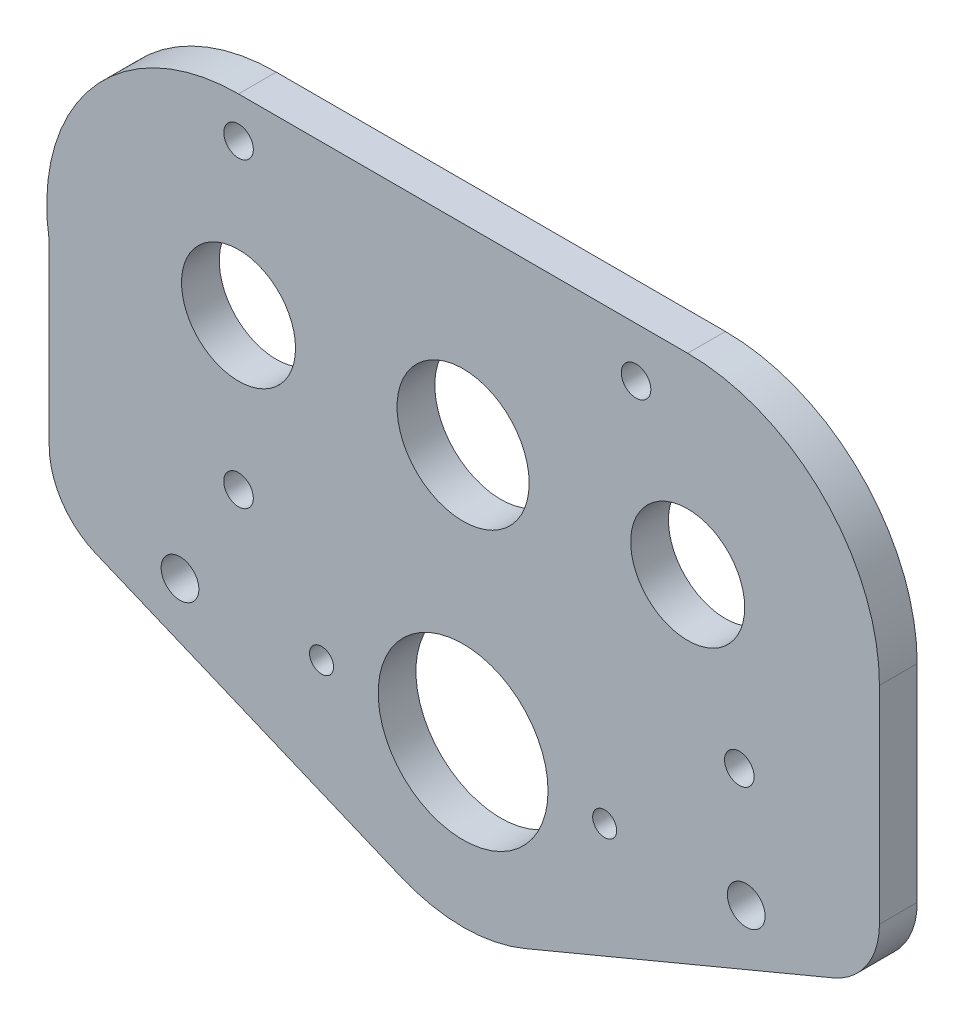
SolidWorks part; units mm, degrees
ref_plane "Front Plane" through (0, 0, 0) normal (0, 0, 1) x (1, 0, 0)
ref_plane "Top Plane" through (0, 0, 0) normal (0, 1, 0) x (1, 0, 0)
ref_plane "Right Plane" through (0, 0, 0) normal (1, 0, 0) x (0, 0, -1)
sketch "Sketch1" plane through (0, 0, 0) normal (0, 0, 1) x (1, 0, 0)
  line L0 (-37.7793, 75.5142) -> (37.7793, 75.5142)
  line L1 (-73.025, -38.1) -> (-73.025, 38.1) construction
  line L2 (-61.8163, -3.4327) -> (-10.3992, -24.9035)
  line L3 (-327.025, 38.1) -> (327.025, 38.1) construction
  line L4 (-327.025, 38.1) -> (-327.025, -38.1) construction
  line L5 (-327.025, -38.1) -> (327.025, -38.1) construction
  line L6 (327.025, 38.1) -> (327.025, -38.1) construction
  line L7 (-327.025, 38.1) -> (327.025, -38.1) construction
  line L8 (-327.025, -38.1) -> (327.025, 38.1) construction
  line L9 (-37.7793, 68.6562) -> (-37.7793, 17.8562) construction
  line L10 (-69.6226, 38.1) -> (-69.6226, 8.2865)
  line L11 (70.0373, 43.2562) -> (70.0373, 8.4595)
  line L12 (62.231, -3.2598) -> (10.3991, -24.9035)
  circle A0 centre (0, 0) radius 14.2875
  circle A1 centre (-37.7793, 43.2562) radius 9.5885
  circle A2 centre (37.7793, 43.2562) radius 9.5885
  circle A3 centre (0, 43.2562) radius 11.1125
  circle A4 centre (-37.7793, 43.2562) radius 32.258 construction
  circle A5 centre (37.7793, 43.2562) radius 32.258 construction
  circle A6 centre (0, 0) radius 6.35 construction
  circle A7 centre (0, 0) radius 39.37 construction
  circle A8 centre (-47.625, 0) radius 3.175
  circle A9 centre (47.625, 0) radius 3.175
  circle A10 centre (0, 0) radius 19.05 construction
  circle A11 centre (0, 43.2562) radius 32.512 construction
  circle A12 centre (-23.8125, 0) radius 2.0193
  circle A13 centre (23.8125, 0) radius 2.0193
  circle A14 centre (0, 0) radius 26.9875 construction
  arc A15 (-10.3992, -24.9035) -> (10.3991, -24.9035) centre (0, 0) ccw
  arc A16 (-69.6226, 38.1) -> (-37.7793, 75.5142) centre (-37.7793, 43.2562) cw
  arc A17 (37.7793, 75.5142) -> (70.0373, 43.2562) centre (37.7793, 43.2562) cw
  circle A18 centre (-37.7793, 68.6562) radius 2.4892
  circle A19 centre (-37.7793, 17.8562) radius 2.4892
  circle A20 centre (37.7793, 68.6562) radius 2.4892 construction
  circle A21 centre (37.7793, 17.8562) radius 2.4892 construction
  circle A22 centre (46.4666, 67.1244) radius 2.4892 [skipped]
  circle A23 centre (54.1061, 62.7137) radius 2.4892 [skipped]
  circle A24 centre (59.7764, 55.9562) radius 2.4892 [skipped]
  circle A25 centre (62.7934, 47.6669) radius 2.4892 [skipped]
  circle A26 centre (62.7934, 38.8455) radius 2.4892 [skipped]
  circle A27 centre (59.7764, 30.5562) radius 2.4892 [skipped]
  circle A28 centre (54.1061, 23.7987) radius 2.4892 [skipped]
  circle A29 centre (46.4666, 19.388) radius 2.4892
  circle A30 centre (37.7793, 17.8562) radius 2.4892 construction
  circle A31 centre (29.092, 19.388) radius 2.4892 [skipped]
  circle A32 centre (21.4525, 23.7987) radius 2.4892 [skipped]
  circle A33 centre (15.7823, 30.5562) radius 2.4892 [skipped]
  circle A34 centre (12.7652, 38.8455) radius 2.4892 [skipped]
  circle A35 centre (12.7652, 47.6669) radius 2.4892 [skipped]
  circle A36 centre (15.7823, 55.9562) radius 2.4892 [skipped]
  circle A37 centre (21.4525, 62.7137) radius 2.4892 [skipped]
  circle A38 centre (29.092, 67.1244) radius 2.4892
  arc A39 (70.0373, 8.4595) -> (62.231, -3.2598) centre (57.3373, 8.4595) cw
  arc A40 (-61.8163, -3.4327) -> (-69.6226, 8.2865) centre (-56.9226, 8.2865) cw
  point P27 (-73.025, -38.1)
  point P87 (37.7793, 43.2562)
  dimension "D1" = 28.575
  dimension "D2" = 22.225
  dimension "D3" = 19.177
  dimension "D4" = 64.516
  dimension "D8" = 12.7
  dimension "D9" = 76.2
  dimension "D11" = 254
  dimension "D12" = 6.35
  dimension "D15" = 65.024
  dimension "D17" = 4.0386
  dimension "D20" = 78.74
  dimension "D23" = 50.8
  dimension "D24" = 4.9784
  dimension "D26" = 12.7
  dimension "D5" = 37.7793
  dimension "D6" = 37.7793
  dimension "D7" = 43.2562
  dimension "D10" = 654.05
  dimension "D13" = 47.625
  dimension "D14" = 47.625
  dimension "D18" = 23.8125
  dimension "D19" = 23.8125
  dimension "D21" = 43.2562
  dimension "D22" = 12.7
  dimension "D16" = 4.7625
  dimension "D25" = 18
extrude "Boss-Extrude1" add sketch "Sketch1" along normal mid plane 6.35
